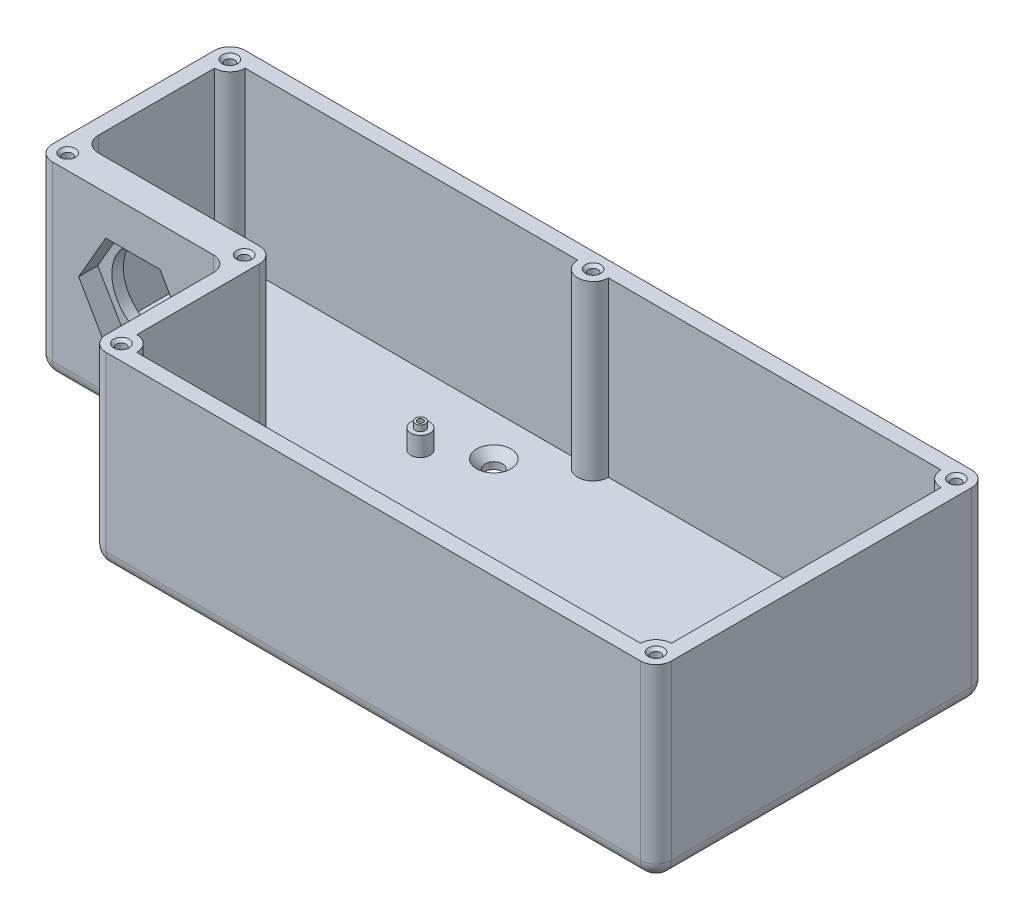
SolidWorks part; units mm, degrees
ref_plane "Alzado" through (0, 0, 0) normal (0, 0, 1) x (1, 0, 0)
ref_plane "Planta" through (0, 0, 0) normal (0, 1, 0) x (1, 0, 0)
ref_plane "Vista lateral" through (0, 0, 0) normal (1, 0, 0) x (0, 0, -1)
sketch "Croquis1" plane through (0, 0, 0) normal (0, 1, 0) x (1, 0, 0)
  line L0 (0.0681, 0.0181) -> (114.3681, 0.0181)
  line L1 (114.3681, 0.0181) -> (114.3681, 48.2781)
  line L2 (114.3681, 48.2781) -> (0.0681, 48.2781)
  line L3 (0.0681, 48.2781) -> (0.0681, 0.0181)
  circle A0 centre (3, 45) radius 1.5
  circle A1 centre (109.6374, 43.2299) radius 1.5
  circle A2 centre (111.3361, 3) radius 1.5
  circle A3 centre (3, 3) radius 1.5
sketch "Croquis2" plane through (0, 0, 0) normal (0, 1, 0) x (1, 0, 0)
  circle A5 centre (3, 3) radius 1.3
  circle A6 centre (3, 3) radius 1.3
  circle A8 centre (111.3361, 3) radius 1.3
  circle A9 centre (111.3361, 3) radius 1.3
  circle A11 centre (109.6374, 43.2299) radius 1.3
  circle A12 centre (109.6374, 43.2299) radius 1.3
  circle A43 centre (3, 45) radius 1.3
  circle A44 centre (3, 45) radius 1.3
  dimension "D1" = 0.2
  dimension "D2" = 0.2
  dimension "D3" = 0.2
  dimension "D4" = 0.2
extrude "Saliente-Extruir1" add sketch "Croquis2" along normal blind 6.5
sketch "Croquis3" plane through (0, 0, 0) normal (0, 1, 0) x (1, 0, 0)
  circle A2 centre (3, 45) radius 2.5
  circle A3 centre (3, 45) radius 2.5
  circle A5 centre (3, 3) radius 2.5
  circle A6 centre (3, 3) radius 2.5
  circle A8 centre (111.3361, 3) radius 2.5
  circle A9 centre (111.3361, 3) radius 2.5
  circle A11 centre (109.6374, 43.2299) radius 2.5
  circle A12 centre (109.6374, 43.2299) radius 2.5
  dimension "D1" = 1
  dimension "D2" = 1
  dimension "D3" = 1
  dimension "D4" = 1
extrude "Saliente-Extruir2" add sketch "Croquis3" along normal blind 5
sketch "Croquis4" plane through (0, 6.5, 0) normal (0, 1, 0) x (1, 0, 0)
  circle A0 centre (3, 45) radius 0.75
  circle A1 centre (3, 3) radius 0.75
  circle A2 centre (111.3361, 3) radius 0.75
  circle A3 centre (109.6374, 43.2299) radius 0.75
  dimension "D1" = 1.5
extrude "Cortar-Extruir1" cut sketch "Croquis4" against normal blind 5
sketch "Croquis5" plane through (0, 0, 0) normal (0, 1, 0) x (1, 0, 0)
  line L0 (114.3681, 48.2781) -> (0.0681, 48.2781) construction
  line L1 (124.3681, 63.2781) -> (-64.9319, 63.2781)
  line L2 (124.3681, 63.2781) -> (124.3681, -14.9819)
  line L3 (124.3681, -14.9819) -> (-14.9319, -14.9819)
  line L4 (-64.9319, 63.2781) -> (-64.9319, 25.0181)
  line L5 (114.3681, 0.0181) -> (114.3681, 48.2781) construction
  line L6 (0.0681, 0.0181) -> (114.3681, 0.0181) construction
  line L7 (0.0681, 48.2781) -> (0.0681, 0.0181) construction
  line L8 (-64.9319, 25.0181) -> (-14.9319, 25.0181)
  line L9 (-14.9319, 25.0181) -> (-14.9319, -14.9819)
  dimension "D1" = 15
  dimension "D2" = 10
  dimension "D3" = 15
  dimension "D4" = 50
  dimension "D5" = 40
  dimension "D6" = 15
extrude "Saliente-Extruir3" add sketch "Croquis5" against normal blind 4
sketch "Croquis6" plane through (0, 0, 0) normal (0, 1, 0) x (1, 0, 0)
  line L6 (-68.9319, 21.0181) -> (-68.9319, 17.0181)
  line L7 (-68.9319, 17.0181) -> (-18.9319, 17.0181)
  line L8 (-64.9319, 25.0181) -> (-14.9319, 25.0181) construction
  line L9 (124.3681, 63.2781) -> (-64.9319, 63.2781) construction
  line L10 (-14.9319, -14.9819) -> (124.3681, -14.9819) construction
  line L11 (124.3681, -14.9819) -> (124.3681, 63.2781) construction
  line L12 (128.3681, -18.9819) -> (128.3681, 67.2781)
  line L13 (128.3681, 67.2781) -> (-68.9319, 67.2781)
  line L14 (-68.9319, 67.2781) -> (-68.9319, 21.0181)
  line L15 (-68.9319, 21.0181) -> (-18.9319, 21.0181)
  line L16 (-18.9319, 21.0181) -> (-18.9319, -18.9819)
  line L17 (-18.9319, -18.9819) -> (128.3681, -18.9819)
  line L18 (128.3681, -18.9819) -> (128.3681, 67.2781)
  line L19 (128.3681, 67.2781) -> (-68.9319, 67.2781)
  line L20 (-68.9319, 67.2781) -> (-68.9319, 21.0181)
  line L22 (-18.9319, 17.0181) -> (-18.9319, -18.9819)
  line L23 (-18.9319, -18.9819) -> (128.3681, -18.9819)
  line L24 (-64.9319, 63.2781) -> (-64.9319, 25.0181) construction
  line L25 (-14.9319, -14.9819) -> (124.3681, -14.9819)
  line L26 (124.3681, -14.9819) -> (124.3681, 63.2781)
  line L27 (124.3681, 63.2781) -> (-64.9319, 63.2781)
  line L28 (-64.9319, 63.2781) -> (-64.9319, 25.0181)
  line L29 (-64.9319, 25.0181) -> (-14.9319, 25.0181)
  line L30 (-14.9319, 25.0181) -> (-14.9319, -14.9819) construction
  line L31 (-14.9319, 25.0181) -> (-14.9319, -14.9819)
  dimension "D2" = 8
  dimension "D1" = 4
extrude "Saliente-Extruir4" add sketch "Croquis6" along normal blind 45 and the other way blind 4
fillet "Redondeo1" radius 4 18 edges at (-18.9319, -4, 0.9819) (54.7181, -4, 18.9819) (128.3681, -4, -24.1481) (29.7181, -4, -67.2781) (-68.9319, -4, -42.1481) (-43.9319, -4, -17.0181) (124.3681, 22.5, 14.9819) (124.3681, 22.5, -63.2781) (-64.9319, 22.5, -63.2781) (-18.9319, 20.5, -17.0181) (128.3681, 20.5, 18.9819) (128.3681, 20.5, -67.2781) (-68.9319, 20.5, -67.2781) (-68.9319, 20.5, -17.0181) (-18.9319, 20.5, 18.9819) (-14.9319, 22.5, -25.0181) (-14.9319, 22.5, 14.9819) (-64.9319, 22.5, -25.0181)
sketch "Croquis7" plane through (0, 0, -17.0181) normal (0, 0, 1) x (1, 0, 0)
  line L0 (-64.9319, 45) -> (-22.9319, 0) construction
  line L1 (-64.9319, 45) -> (-22.9319, 45) construction
  line L2 (-58.077, 22.5) -> (-51.0044, 10.25)
  line L3 (-51.0044, 10.25) -> (-36.8594, 10.25)
  line L4 (-36.8594, 10.25) -> (-29.7868, 22.5)
  line L5 (-29.7868, 22.5) -> (-36.8594, 34.75)
  line L6 (-36.8594, 34.75) -> (-51.0044, 34.75)
  line L7 (-51.0044, 34.75) -> (-58.077, 22.5)
  circle A0 centre (-43.9319, 22.5) radius 12.25 construction
  dimension "D1" = 24.5
extrude "Cortar-Extruir2" cut sketch "Croquis7" against normal blind 5
sketch "Croquis8" plane through (0, 0, -22.0181) normal (0, 0, 1) x (1, 0, 0)
  line L0 (-58.077, 22.5) -> (-29.7868, 22.5) construction
  circle A0 centre (-43.9319, 22.5) radius 10.5
  point P6 (0, 0)
  point P7 (-43.9319, 20)
  dimension "D1" = 21
extrude "Cortar-Extruir3" cut sketch "Croquis8" against normal blind 5
sketch "Croquis9" plane through (0, 45, 0) normal (0, 1, 0) x (1, 0, 0)
  line L0 (120.3681, 63.2781) -> (-60.9319, 63.2781) construction
  line L1 (-64.9319, 63.2781) -> (29.7181, 63.2781) construction
  line L2 (29.7181, 63.2781) -> (124.3681, 63.2781) construction
  circle A0 centre (-64.9319, 63.2781) radius 4
  circle A1 centre (124.3681, 63.2781) radius 4
  circle A2 centre (124.3681, -14.9819) radius 4
  circle A3 centre (-64.9319, 21.0181) radius 4
  circle A4 centre (-18.9319, 21.0181) radius 4
  circle A5 centre (-14.9319, -14.9819) radius 4
  circle A6 centre (29.7181, 63.2781) radius 4
  dimension "D1" = 8
extrude "Saliente-Extruir6" add sketch "Croquis9" against normal up to surface (45 mm away) up to face at (109.6374, 0, -45.7299)
hole_wizard "Refrentado para tornillo tapón con cabeza plana de clavija de M31" positions "Croquis10" profile "Croquis11" countersink size "M3" standard "Ansi Metric"
sketch "Croquis10" plane through (0, 45, 0) normal (0, 1, 0) x (1, 0, 0)
  point P0 (-64.9319, 21.0181)
  point P3 (-64.9319, 63.2781)
  point P6 (29.7181, 63.2781)
  point P9 (124.3681, 63.2781)
  point P12 (124.3681, -14.9819)
  point P15 (-14.9319, -14.9819)
  point P18 (-18.9319, 21.0181)
sketch "Croquis11" plane through (-64.9319, 45, -21.0181) normal (1, 0, 0) x (0, 0, 1)
  line L0 (0, 0) -> (0, 10.7511)
  line L1 (0, 10.7511) -> (1.25, 10)
  line L2 (1.25, 10) -> (1.25, 0.75)
  line L3 (1.25, 0.75) -> (2, 0)
  line L5 (2, 0) -> (0, 0)
  line L6 (-1.25, 0.75) -> (-2, 0) construction
  line L10 (0, 10.7511) -> (-1.25, 10) construction
  line L11 (0, -6.35) -> (0, 107.95) construction
  dimension "Diámetro de taladro" = 2.5
  dimension "Profundidad de taladro" = 10
  dimension "Ángulo de avellanado cercano" = 4
  dimension "Ángulo de avellanado lejano" = 90
  dimension "Ángulo de perforador" = 118
sketch "Croquis12" plane through (0, 0, 0) normal (0, 1, 0) x (1, 0, 0)
  line L0 (94.8031, 52.5081) -> (94.8031, 63.2781) construction
  line L1 (14.6331, 52.5081) -> (94.8031, 52.5081) construction
  line L2 (14.6331, 52.5081) -> (14.6331, -4.2119) construction
  line L3 (14.6331, -4.2119) -> (94.8031, -4.2119) construction
  line L4 (94.8031, 52.5081) -> (94.8031, -4.2119) construction
  line L5 (29.7181, 63.2781) -> (124.3681, 63.2781) construction
  line L6 (94.8031, -4.2119) -> (94.8031, -14.9819) construction
  line L7 (-10.9319, -14.9819) -> (120.3681, -14.9819) construction
  line L8 (94.8031, -4.2119) -> (124.3681, -4.2119) construction
  line L9 (124.3681, -10.9819) -> (124.3681, 59.2781) construction
  line L10 (14.6331, -4.2119) -> (-14.9319, -4.2119) construction
  line L11 (-14.9319, 21.0181) -> (-14.9319, -10.9819) construction
  dimension "D1" = 56.72
  dimension "D2" = 80.17
hole_wizard "Refrentado para tornillo tapón con cabeza plana de clavija de M41" positions "Croquis13" profile "Croquis14" countersink size "M4" standard "Ansi Metric"
sketch "Croquis13" plane through (0, 0, 0) normal (0, 1, 0) x (1, 0, 0)
  point P0 (14.6331, 52.5081)
  point P3 (94.8031, 52.5081)
  point P6 (94.8031, -4.2119)
  point P9 (14.6331, -4.2119)
sketch "Croquis14" plane through (14.6331, 0, -52.5081) normal (1, 0, 0) x (0, 0, 1)
  line L0 (0, 0) -> (0, 11.3519)
  line L1 (0, 11.3519) -> (2.25, 10)
  line L2 (2.25, 10) -> (2.25, 2.23)
  line L3 (2.25, 2.23) -> (4.48, 0)
  line L5 (4.48, 0) -> (0, 0)
  line L6 (-2.25, 2.23) -> (-4.48, 0) construction
  line L10 (0, 11.3519) -> (-2.25, 10) construction
  line L11 (0, -6.35) -> (0, 107.95) construction
  dimension "Diámetro de taladro" = 4.5
  dimension "Profundidad de taladro" = 10
  dimension "Ángulo de avellanado cercano" = 8.96
  dimension "Ángulo de avellanado lejano" = 90
  dimension "Ángulo de perforador" = 118
